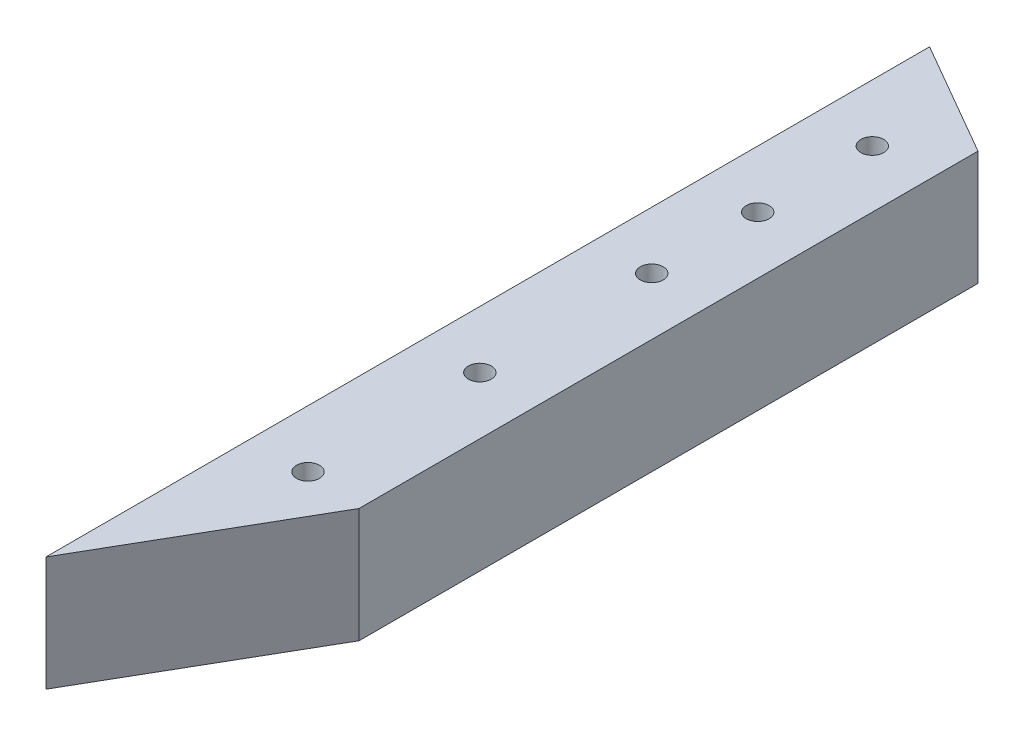
SolidWorks part; units mm, degrees
ref_plane "前视基准面" through (0, 0, 0) normal (0, 0, 1) x (1, 0, 0)
ref_plane "上视基准面" through (0, 0, 0) normal (0, 1, 0) x (1, 0, 0)
ref_plane "右视基准面" through (0, 0, 0) normal (1, 0, 0) x (0, 0, -1)
other "Configuration Table"
sketch "草图1" plane through (0, 0, 0) normal (0, 0, 1) x (1, 0, 0)
  line L1 (0, 0) -> (20, 0)
  line L2 (0, 0) -> (0, 20)
  line L3 (0, 20) -> (20, 20)
  line L4 (20, 0) -> (20, 20)
  dimension "D1" = 20
extrude "凸台-拉伸1" add sketch "草图1" along normal blind 154.23
sketch "草图2" plane through (0, 20, 0) normal (0, 1, 0) x (1, 0, 0)
  line L0 (0, -154.23) -> (20, -119.589)
  line L1 (20, -154.23) -> (20, 0) construction
  line L2 (20, -119.589) -> (20, -154.23)
  line L3 (20, -154.23) -> (0, -154.23)
  line L4 (20, -11.547) -> (0, 0)
  line L5 (0, 0) -> (20, 0)
  line L6 (20, 0) -> (20, -11.547)
  line L7 (0, -154.23) -> (0, 0) construction
  dimension "D1" = 60
  dimension "D2" = 60
extrude "切除-拉伸1" cut sketch "草图2" against normal blind 154.23
sketch "草图3" plane through (0, 20, 0) normal (0, 1, 0) x (1, 0, 0)
  line L0 (10, -5.7735) -> (10, -136.9095) construction
  line L1 (0, 0) -> (20, -11.547) construction
  line L2 (20, -119.589) -> (0, -154.23) construction
  circle A2 centre (10, -88.5) radius 2
  circle A3 centre (10, -118.5) radius 2
  circle A4 centre (10, -58.5) radius 2
  circle A5 centre (10, -20) radius 2
  circle A6 centre (10, -40) radius 2
  dimension "D6" = 4
  dimension "D4" = 18.5
  dimension "D1" = 35.73
  dimension "D2" = 30
  dimension "D3" = 30
  dimension "D8" = 20
extrude "切除-拉伸2" cut sketch "草图3" against normal through all both
